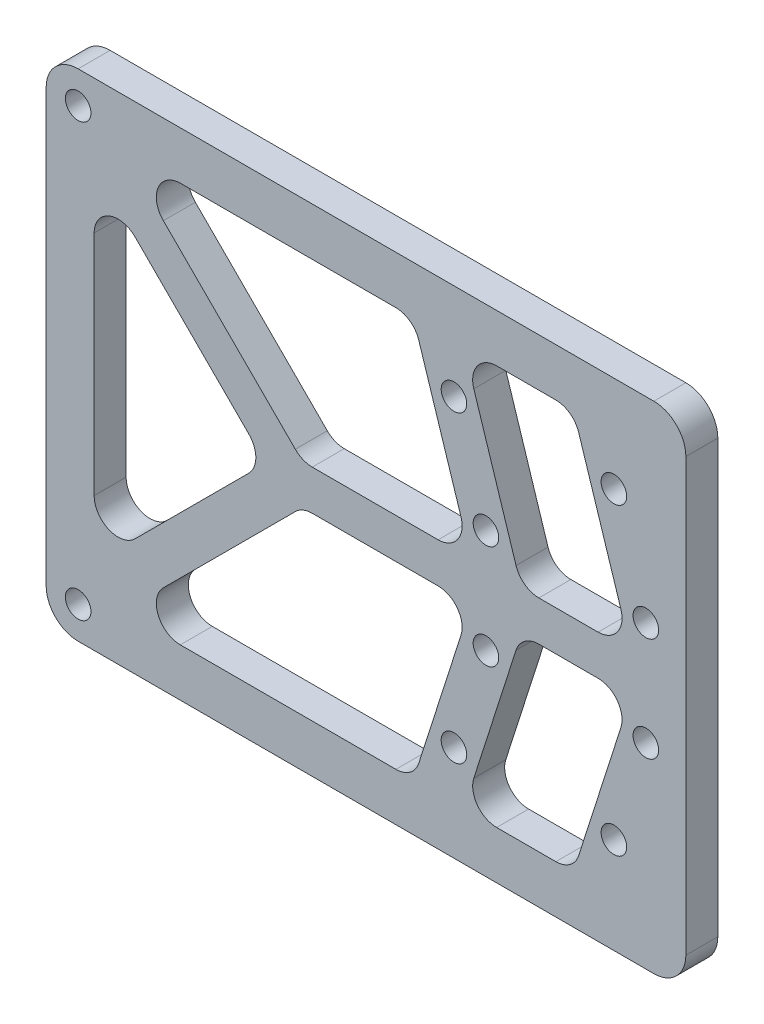
SolidWorks part; units mm, degrees
material "Thornel Mat VMA"
ref_plane "前视基准面" through (0, 0, 0) normal (0, 0, 1) x (1, 0, 0)
ref_plane "上视基准面" through (0, 0, 0) normal (0, 1, 0) x (1, 0, 0)
ref_plane "右视基准面" through (0, 0, 0) normal (1, 0, 0) x (0, 0, -1)
sketch "草图1" plane through (0, 0, 0) normal (0, 0, 1) x (1, 0, 0)
  line L1 (-40, -31) -> (40, -31)
  line L2 (-40, -31) -> (-40, 31)
  line L3 (-40, 31) -> (40, 31)
  line L4 (40, -31) -> (40, 31)
  line L5 (0, 31) -> (0, -31) construction
  line L6 (-40, 0) -> (40, 0) construction
  point P0 (0, 0)
  dimension "D1" = 62
  dimension "D2" = 80
extrude "凸台-拉伸1" add sketch "草图1" along normal blind 4
fillet "圆角1" radius 4 2 edges at (-40, -31, 2) (-40, 31, 2)
fillet "圆角2" radius 4 2 edges at (40, -31, 2) (40, 31, 2)
sketch "草图2" plane through (0, 0, 4) normal (0, 0, 1) x (1, 0, 0)
  line L0 (0, 0) -> (40, 0) construction
  line L1 (40, -27) -> (40, 27) construction
  line L2 (15, 6.5) -> (15, 0) construction
  line L3 (35, 6.5) -> (35, 0) construction
  line L4 (11, 19) -> (11, 0) construction
  line L5 (11, 0) -> (11, -19) construction
  line L6 (15, 0) -> (15, -6.5) construction
  line L7 (35, 0) -> (35, -6.5) construction
  line L8 (31, 0) -> (31, -19) construction
  line L9 (31, 19) -> (31, 0) construction
  circle A6 centre (11, -19) radius 1.6
  circle A7 centre (31, -19) radius 1.6
  circle A8 centre (35, 6.5) radius 1.6
  circle A9 centre (15, 6.5) radius 1.6
  circle A10 centre (11, 19) radius 1.6
  circle A11 centre (31, 19) radius 1.6
  circle A12 centre (15, -6.5) radius 1.6
  circle A13 centre (35, -6.5) radius 1.6
  dimension "D9" = 3.2
  dimension "D1" = 11
  dimension "D2" = 19
  dimension "D3" = 15
  dimension "D4" = 6.5
  dimension "D5" = 31
  dimension "D6" = 19
  dimension "D7" = 35
  dimension "D8" = 6.5
extrude "切除-拉伸1" cut sketch "草图2" against normal blind 10
sketch "草图3" plane through (0, 0, 4) normal (0, 0, 1) x (1, 0, 0)
  line L0 (0, 0) -> (-36, 0) construction
  line L1 (-36, 0) -> (-36, -27) construction
  circle A2 centre (-36, -27) radius 1.6
  circle A3 centre (-36, 27) radius 1.6
  dimension "D3" = 3.2
  dimension "D1" = 36
  dimension "D2" = 27
extrude "切除-拉伸2" cut sketch "草图3" against normal blind 10
sketch "草图4" plane through (0, 0, 4) normal (0, 0, 1) x (1, 0, 0)
  line L0 (-34, 25) -> (5.9301, 25)
  line L1 (5.9301, 25) -> (13.9301, 0)
  line L2 (13.9301, 0) -> (5.9301, -25)
  line L3 (5.9301, -25) -> (-34, -25)
  line L4 (-34, -25) -> (-34, 25)
  line L5 (-40, 27) -> (-40, -27) construction
  line L6 (36, 31) -> (-36, 31) construction
  line L7 (-36, -31) -> (36, -31) construction
  line L8 (0, 0) -> (13.9301, 0) construction
  line L9 (11, 19) -> (15, 6.5) construction
  line L10 (-34, 25) -> (-9, 0) construction
  line L11 (-9, 0) -> (-34, -25) construction
  line L12 (-9, 0) -> (13.9301, 0) construction
  line L13 (-9, -2.5) -> (13.9301, -2.5)
  line L14 (-9, 2.5) -> (13.9301, 2.5)
  line L15 (-35.7678, 23.2322) -> (-10.7678, -1.7678)
  line L16 (-32.2322, 26.7678) -> (-7.2322, 1.7678)
  line L17 (-10.7678, 1.7678) -> (-35.7678, -23.2322)
  line L18 (-7.2322, -1.7678) -> (-32.2322, -26.7678)
  dimension "D1" = 6
  dimension "D2" = 6
  dimension "D3" = 6
  dimension "D4" = 3
  dimension "D5" = 2.5
  dimension "D6" = 2.5
  dimension "D7" = 2.5
  dimension "D8" = 2.5
  dimension "D9" = 2.5
  dimension "D10" = 2.5
extrude "切除-拉伸3" cut sketch "草图4" against normal blind 10 contours L17 L15 L4 | L0 L16 L14 L1 | L13 L18 L3 L2
fillet "圆角3" radius 3 11 edges at (5.9301, -25, 2) (-30.4645, -25, 2) (-7.9645, -2.5, 2) (13.1301, -2.5, 2) (-30.4645, 25, 2) (5.9301, 25, 2) (-34, 21.4645, 2) (-12.5355, 0, 2) (-34, -21.4645, 2) (-7.9645, 2.5, 2) (13.1301, 2.5, 2)
sketch "草图5" plane through (0, 0, 4) normal (0, 0, 1) x (1, 0, 0)
  line L0 (0, 0) -> (40, 0) construction
  line L1 (40, -27) -> (40, 27) construction
  line L2 (12.2299, 25) -> (20.2299, 0)
  line L3 (20.2299, 0) -> (12.2299, -25)
  line L4 (12.2299, -25) -> (25.9301, -25)
  line L5 (25.9301, -25) -> (33.9301, 0)
  line L6 (33.9301, 0) -> (25.9301, 25)
  line L7 (25.9301, 25) -> (12.2299, 25)
  line L8 (-23.2218, 25) -> (3.7403, 25) construction
  line L9 (3.7403, -25) -> (-23.2218, -25) construction
  line L10 (11, 19) -> (15, 6.5) construction
  line L11 (19.4299, 2.5) -> (33.1301, 2.5)
  line L12 (19.4299, -2.5) -> (33.1301, -2.5)
  circle A0 centre (31, 19) radius 1.6 construction
  dimension "D1" = 3
  dimension "D2" = 3
  dimension "D3" = 2.5
extrude "切除-拉伸4" cut sketch "草图5" against normal blind 10 contours L12 L3 L4 L5 | L2 L11 L6 L7
fillet "圆角4" radius 3 8 edges at (25.9301, -25, 2) (12.2299, -25, 2) (19.4299, -2.5, 2) (33.1301, -2.5, 2) (12.2299, 25, 2) (25.9301, 25, 2) (19.4299, 2.5, 2) (33.1301, 2.5, 2)
